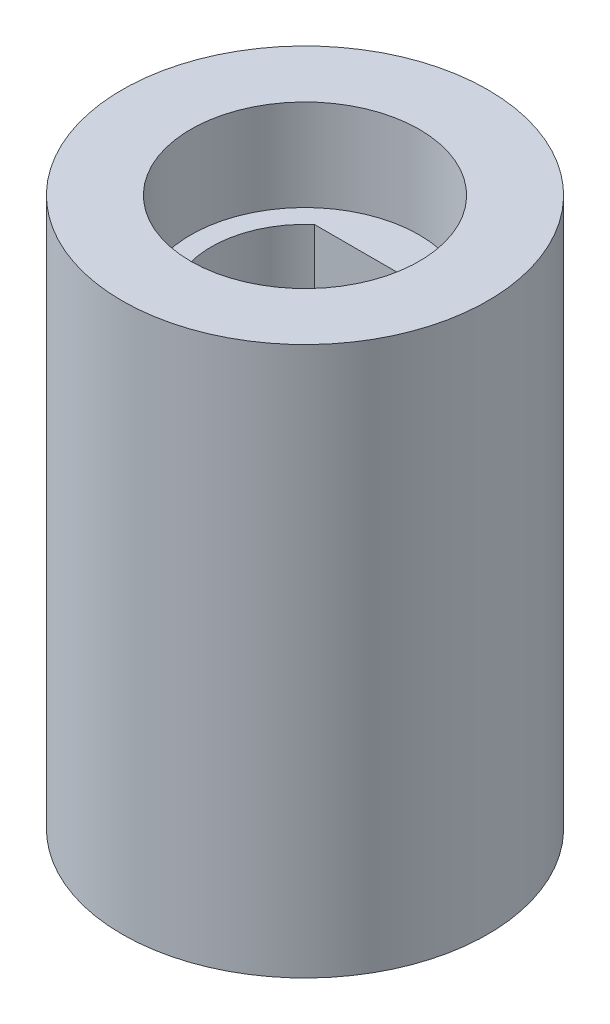
SolidWorks part; units mm, degrees
ref_plane "Front Plane" through (0, 0, 0) normal (0, 0, 1) x (1, 0, 0)
ref_plane "Top Plane" through (0, 0, 0) normal (0, 1, 0) x (1, 0, 0)
ref_plane "Right Plane" through (0, 0, 0) normal (1, 0, 0) x (0, 0, -1)
sketch "Sketch1" plane through (0, 0, 0) normal (0, 1, 0) x (1, 0, 0)
  line L0 (-1.3416, 1.55) -> (1.3416, 1.55)
  arc A0 (-1.3416, 1.55) -> (1.3416, 1.55) centre (0, 0) ccw
  circle A1 centre (0, 0) radius 4
  point P1 (0, -2.05)
  dimension "D1" = 4.1
  dimension "D3" = 8
  dimension "D2" = 3.6
extrude "Boss-Extrude1" add sketch "Sketch1" along normal blind 10
sketch "Sketch2" plane through (0, 10, 0) normal (0, 1, 0) x (1, 0, 0)
  circle A0 centre (0, 0) radius 2.5
  circle A1 centre (0, 0) radius 4
  dimension "D1" = 5
extrude "Boss-Extrude2" add sketch "Sketch2" along normal blind 2
